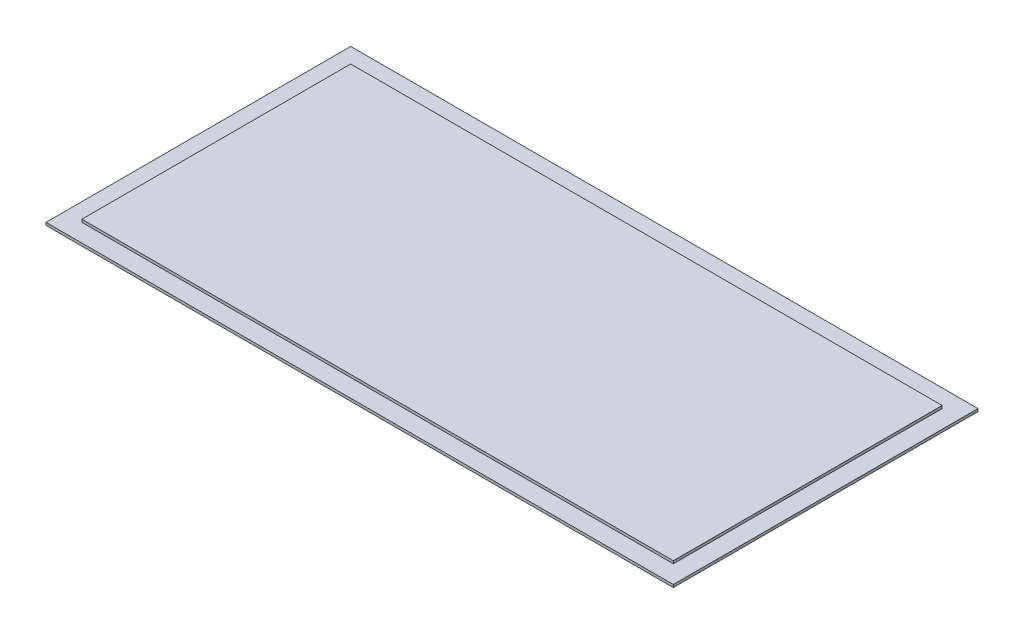
SolidWorks part; units mm, degrees
ref_plane "Спереди" through (0, 0, 0) normal (0, 0, 1) x (1, 0, 0)
ref_plane "Сверху" through (0, 0, 0) normal (0, 1, 0) x (1, 0, 0)
ref_plane "Справа" through (0, 0, 0) normal (1, 0, 0) x (0, 0, -1)
sketch "Эскиз1" plane through (0, 0, 0) normal (0, 1, 0) x (1, 0, 0)
  line L1 (350, 170) -> (-350, 170)
  line L2 (350, 170) -> (350, -170)
  line L3 (350, -170) -> (-350, -170)
  line L4 (-350, 170) -> (-350, -170)
  line L5 (350, 170) -> (-350, -170) construction
  line L6 (350, -170) -> (-350, 170) construction
  point P0 (0, 0)
  dimension "D1" = 700
  dimension "D2" = 340
extrude "Бобышка-Вытянуть1" add sketch "Эскиз1" along normal blind 3
sketch "Эскиз2" plane through (0, 3, 0) normal (0, 1, 0) x (1, 0, 0)
  line L1 (330, 150) -> (-330, 150)
  line L2 (330, 150) -> (330, -150)
  line L3 (330, -150) -> (-330, -150)
  line L4 (-330, 150) -> (-330, -150)
  line L5 (330, 150) -> (-330, -150) construction
  line L6 (330, -150) -> (-330, 150) construction
  point P0 (0, 0)
  dimension "D1" = 660
  dimension "D2" = 300
extrude "Бобышка-Вытянуть2" add sketch "Эскиз2" along normal blind 3
